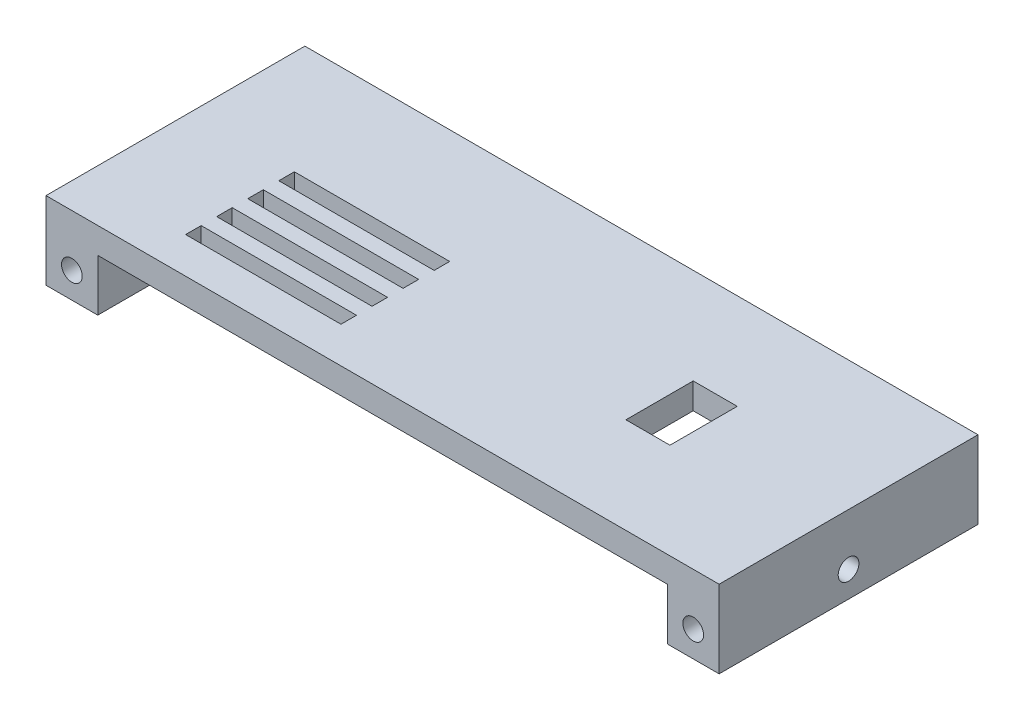
SolidWorks part; units mm, degrees
other "Marcação1"
sketch "Esboço3" plane through (-130, 13, -50) normal (0, 1, 0) x (1, 0, 0)
sketch "Esboço4" plane through (-130, 15, -50) normal (0, 1, 0) x (1, 0, 0)
sketch "Esboço8" plane through (-130, 15, -50) normal (0, 1, 0) x (1, 0, 0)
sketch "Esboço18" plane through (-130, 15, -50) normal (0, 1, 0) x (1, 0, 0)
sketch "Esboço21" plane through (-130, 15, -50) normal (0, 1, 0) x (1, 0, 0)
other "Marcação2"
sketch "Esboço17" plane through (-130, 0, -50) normal (-1, 0, 0) x (0, 0, 1)
sketch "Esboço19" plane through (-130, 0, -50) normal (-1, 0, 0) x (0, 0, 1)
sketch "Esboço22" plane through (-130, 0, -50) normal (-1, 0, 0) x (0, 0, 1)
ref_plane "Plano frontal" through (0, 0, 0) normal (0, 0, 1) x (1, 0, 0)
ref_plane "Plano superior" through (0, 0, 0) normal (0, 1, 0) x (1, 0, 0)
ref_plane "Plano direito" through (0, 0, 0) normal (1, 0, 0) x (0, 0, -1)
sketch "Esboço1" plane through (0, 0, 0) normal (0, 1, 0) x (1, 0, 0)
  line L1 (-130, 50) -> (0, 50)
  line L2 (-130, 50) -> (-130, 0)
  line L3 (-130, 0) -> (0, 0)
  line L4 (0, 50) -> (0, 0)
extrude "Ressalto-extrusão1" add sketch "Esboço1" along normal blind 15
sketch "Esboço2" plane through (0, 0, -50) normal (0, 0, -1) x (-1, 0, 0)
  line L1 (10, 0) -> (10, 15) construction
  line L2 (0, 0) -> (130, 0) construction
  line L3 (0, 15) -> (130, 15) construction
  line L4 (120, 0) -> (120, 15) construction
  line L5 (0, 15) -> (0, 0) construction
  line L6 (130, 15) -> (130, 0) construction
  line L7 (0, 10) -> (130, 10) construction
  line L9 (10, 0) -> (120, 0)
  line L10 (10, 0) -> (10, 10)
  line L11 (10, 10) -> (120, 10)
  line L12 (120, 0) -> (120, 10)
  dimension "D1" = 10
  dimension "D2" = 10
  dimension "D3" = 10
extrude "Corte-extrusão1" cut sketch "Esboço2" against normal blind 51
sketch "Esboço6" plane through (0, 0, -50) normal (0, 0, -1) x (-1, 0, 0)
  circle A1 centre (5, 5) radius 2
  circle A2 centre (125, 5) radius 2
sketch "Esboço7" plane through (0, 0, 0) normal (0, 0, 1) x (1, 0, 0)
  circle A0 centre (-5, 5) radius 2
  circle A1 centre (-125, 5) radius 2
ref_plane "Plano1" through (0, 15, 0) normal (0, 0, -1) x (-1, 0, 0)
sketch "Esboço12" plane through (0, 0, 0) normal (1, 0, 0) x (0, 0, -1)
  circle A0 centre (25, 5) radius 2
sketch "Esboço14" plane through (-130, 0, 0) normal (-1, 0, 0) x (0, 0, 1)
  circle A0 centre (-25, 5) radius 2
extrude "Corte-extrusão8" cut sketch "Esboço12" against normal blind 10 contours A0
extrude "Corte-extrusão9" cut sketch "Esboço14" against normal blind 10 contours A0
extrude "Corte-extrusão11" cut sketch "Esboço7" against normal blind 10
extrude "Corte-extrusão12" cut sketch "Esboço6" against normal blind 10 contours A2 | A1
sketch "Esboço20" plane through (0, 15, 0) normal (0, 1, 0) x (1, 0, 0)
  line L0 (-130, 15.2243) -> (-110, 15.2243) construction
  line L1 (-110, 15.9665) -> (-110, 18.9665) construction
  line L2 (-110, 21.9665) -> (-110, 24.9665) construction
  line L3 (-110, 18.9665) -> (-80, 18.9665)
  line L10 (-110, 18.9665) -> (-110, 21.9665)
  line L11 (-110, 21.9665) -> (-80, 21.9665)
  line L12 (-80, 18.9665) -> (-80, 21.9665)
  line L17 (-130, 50) -> (-130, 0) construction
  line L18 (-80, 9.9665) -> (-80, 12.9665) construction
  line L19 (-110, 9.9665) -> (-80, 9.9665)
  line L20 (-110, 9.9665) -> (-110, 6.9665)
  line L21 (-110, 6.9665) -> (-80, 6.9665)
  line L22 (-80, 9.9665) -> (-80, 6.9665)
  line L23 (-110, 24.9665) -> (-80, 24.9665)
  line L24 (-80, 12.9665) -> (-110, 12.9665)
  line L25 (-80, 12.9665) -> (-80, 15.9665)
  line L26 (-80, 15.9665) -> (-110, 15.9665)
  line L27 (-110, 12.9665) -> (-110, 15.9665)
  line L28 (-110, 24.9665) -> (-110, 27.9665)
  line L29 (-110, 27.9665) -> (-80, 27.9665)
  line L30 (-80, 24.9665) -> (-80, 27.9665)
  dimension "D1" = 20
  dimension "D2" = 30
  dimension "D5" = 3
  dimension "D6" = 3
  dimension "D7" = 3
  dimension "D8" = 30
  dimension "D9" = 3
  dimension "D10" = 3
  dimension "D11" = 3
  dimension "D12" = 3
sketch "Esboço23" plane through (0, 15, 0) normal (0, 1, 0) x (1, 0, 0)
  line L0 (-28, 0) -> (-28, 50) construction
  line L1 (-130, 0) -> (0, 0) construction
  line L2 (0, 50) -> (-130, 50) construction
  line L3 (0, 18.5) -> (-56.5069, 18.5) construction
  line L4 (0, 0) -> (0, 50) construction
  line L5 (0, 31.5) -> (-56.5069, 31.5) construction
  line L6 (-36.5, 50) -> (-36.5, 0) construction
  line L8 (-36.5, 31.5) -> (-28, 31.5)
  line L9 (-36.5, 31.5) -> (-36.5, 18.5)
  line L10 (-36.5, 18.5) -> (-28, 18.5)
  line L11 (-28, 31.5) -> (-28, 18.5)
  dimension "D1" = 28
  dimension "D2" = 18.5
  dimension "D3" = 8.5
  dimension "D4" = 13
extrude "Corte-extrusão13" cut sketch "Esboço23" against normal blind 10
extrude "Corte-extrusão14" cut sketch "Esboço20" against normal blind 10
